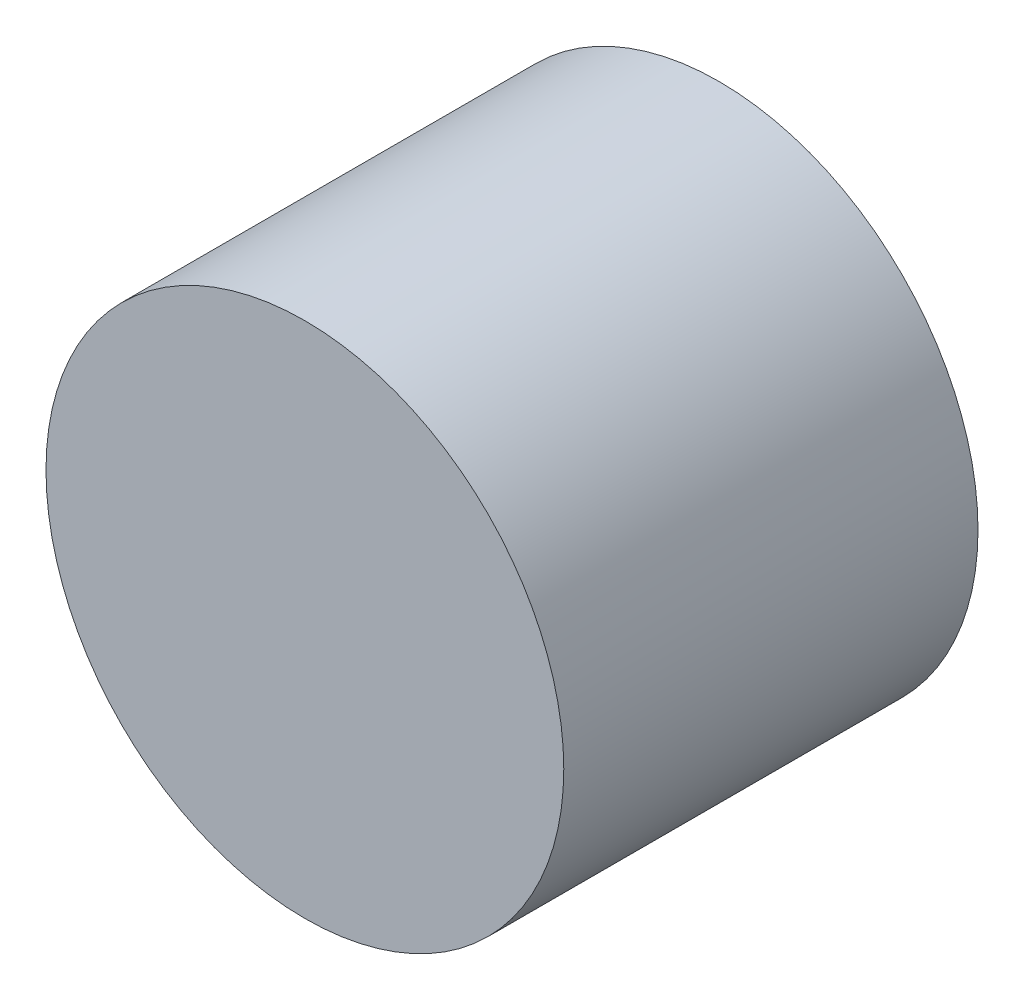
SolidWorks part; units mm, degrees
material "AISI typ 316L nerezová ocel"
ref_plane "Přední rovina" through (0, 0, 0) normal (0, 0, 1) x (1, 0, 0)
ref_plane "Horní rovina" through (0, 0, 0) normal (0, 1, 0) x (1, 0, 0)
ref_plane "Pravá rovina" through (0, 0, 0) normal (1, 0, 0) x (0, 0, -1)
sketch "Skica1" plane through (0, 0, 0) normal (0, 0, 1) x (1, 0, 0)
  circle A0 centre (-20.1538, 15.5029) radius 2.5 construction
  circle A1 centre (-20.1538, 15.5029) radius 2.5
extrude "Přidat vysunutím1" add sketch "Skica1" along normal up to surface (2.0012 mm away) and the other way up to surface (1.9988 mm away)
